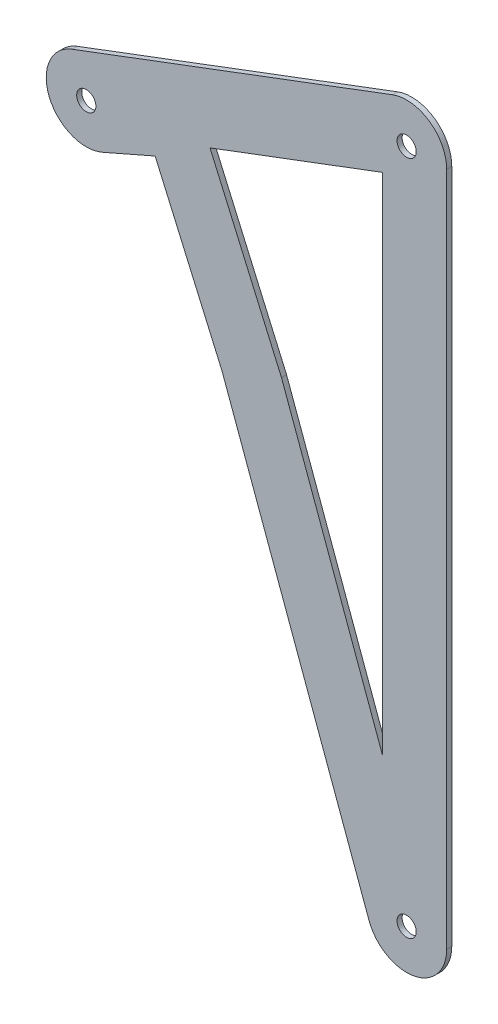
SolidWorks part; units mm, degrees
ref_plane "Front Plane" through (0, 0, 0) normal (0, 0, 1) x (1, 0, 0)
ref_plane "Top Plane" through (0, 0, 0) normal (0, 1, 0) x (1, 0, 0)
ref_plane "Right Plane" through (0, 0, 0) normal (1, 0, 0) x (0, 0, -1)
sketch "Sketch1" plane through (0, 0, 0) normal (0, 0, 1) x (1, 0, 0)
  line L1 (12.5, 0) -> (12.5, 210.8897)
  line L2 (-4.408, 222.5867) -> (-104.408, 184.9021)
  line L3 (-100, 173.2051) -> (0, 173.2051) construction
  line L4 (0, 173.2051) -> (0, 0) construction
  line L5 (-100, 173.2051) -> (0, 0) construction
  line L7 (0, 210.8897) -> (0, 173.2051) construction
  line L15 (-57.6389, 121.342) -> (-78.4975, 168.9751)
  line L16 (-57.6389, 121.342) -> (-11.741, -4.2894)
  line L17 (-39.0677, 128.792) -> (-7.5, 42.385)
  line L18 (-7.5, 42.385) -> (-7.5, 200.0484)
  line L19 (-7.5, 200.0484) -> (-61.3797, 179.7441)
  line L20 (-94.9859, 161.7548) -> (-78.4975, 168.9751)
  line L21 (-61.3797, 179.7441) -> (-61.3797, 179.7441)
  line L22 (-39.0677, 128.792) -> (-61.3797, 179.7441)
  arc A0 (-11.741, -4.2894) -> (12.5, 0) centre (0, 0) ccw
  arc A1 (-104.408, 184.9021) -> (-94.9859, 161.7548) centre (-100, 173.2051) ccw
  arc A2 (12.5, 210.8897) -> (-4.408, 222.5867) centre (0, 210.8897) ccw
  circle A3 centre (-100, 173.2051) radius 3
  circle A4 centre (0, 210.8897) radius 3
  circle A5 centre (0, 0) radius 3
  arc A6 (-7.5, 42.385) -> (-7.5, 42.385) centre (-7.5, 42.385) ccw
  arc A7 (-7.5, 200.0484) -> (-7.5, 200.0484) centre (-7.5, 200.0484) ccw
  arc A8 (-61.3797, 179.7441) -> (-61.3797, 179.7441) centre (-61.3797, 179.7441) cw
  dimension "D1" = 12.5
  dimension "D2" = 6
  dimension "D3" = 200
  dimension "D4" = 173.2051
  dimension "D5" = 20.649
  dimension "D6" = 3
  dimension "D8" = 52
  dimension "D9" = 20
  dimension "D7" = 18
extrude "Boss-Extrude1" add sketch "Sketch1" along normal blind 1.5875
